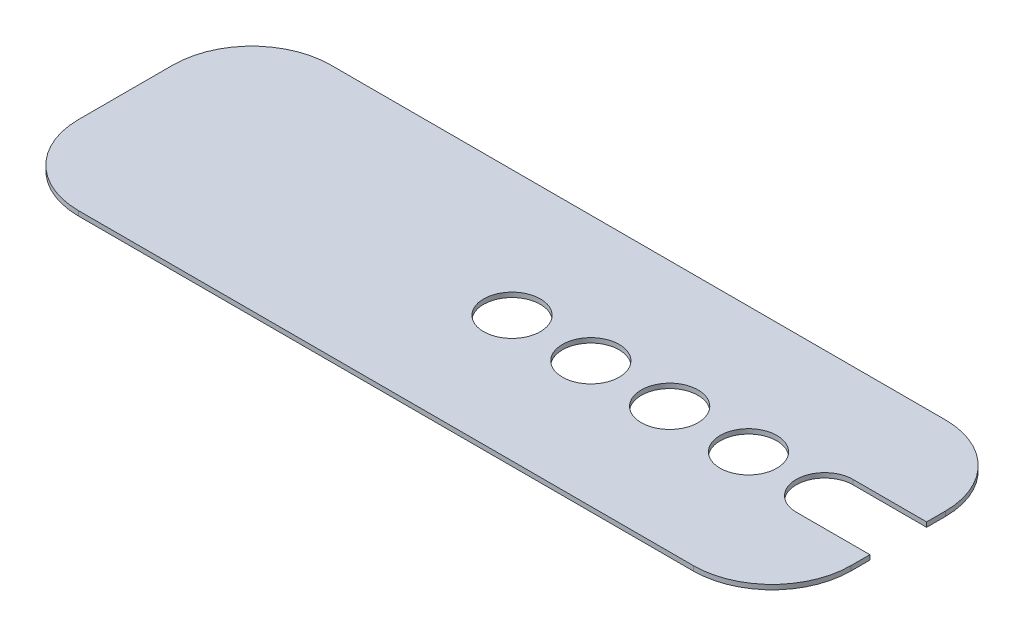
SolidWorks part; units mm, degrees
material "Plain Carbon Steel"
ref_plane "Front Plane" through (0, 0, 0) normal (0, 0, 1) x (1, 0, 0)
ref_plane "Top Plane" through (0, 0, 0) normal (0, 1, 0) x (1, 0, 0)
ref_plane "Right Plane" through (0, 0, 0) normal (1, 0, 0) x (0, 0, -1)
sketch "Sketch1" plane through (0, 0, 0) normal (0, 1, 0) x (1, 0, 0)
  line L1 (-97.5, 40) -> (97.5, 40)
  line L2 (-122.5, 15) -> (-122.5, -15)
  line L3 (-97.5, -40) -> (97.5, -40)
  line L4 (122.5, 15) -> (122.5, -15)
  line L5 (-122.5, 40) -> (122.5, -40) construction
  line L6 (-122.5, -40) -> (122.5, 40) construction
  arc A0 (122.5, 15) -> (97.5, 40) centre (97.5, 15) ccw
  arc A1 (97.5, -40) -> (122.5, -15) centre (97.5, -15) ccw
  arc A2 (-97.5, -40) -> (-122.5, -15) centre (-97.5, -15) cw
  arc A3 (-97.5, 40) -> (-122.5, 15) centre (-97.5, 15) ccw
  point P0 (0, 0)
  dimension "D3" = 25
  dimension "D1" = 80
  dimension "D2" = 245
extrude "Boss-Extrude1" add sketch "Sketch1" along normal blind 1.5
sketch3d "3DSketch1"
  point P0 (71.5552, 1.5, -21.9092)
sketch "Sketch2" plane through (0, 1.5, 0) normal (0, 1, 0) x (1, 0, 0)
  line L0 (122.5, -15) -> (122.5, 15) construction
  line L1 (99.15, -9) -> (122.5, -9)
  line L3 (99.15, 9) -> (122.5, 9)
  line L4 (122.5, 9) -> (122.5, -9)
  circle A0 centre (75, 0) radius 9
  circle A1 centre (50, 0) radius 9
  circle A2 centre (25, 0) radius 9
  circle A3 centre (0, 0) radius 9
  arc A4 (99.15, 9) -> (99.15, -9) centre (99.15, 0) ccw
  dimension "D5" = 18
  dimension "D6" = 18
  dimension "D7" = 18
  dimension "D8" = 18
  dimension "D9" = 23.35
  dimension "D1" = 47.5
  dimension "D2" = 25
  dimension "D3" = 25
  dimension "D4" = 25
extrude "Cut-Extrude3" cut sketch "Sketch2" against normal blind 1.5
